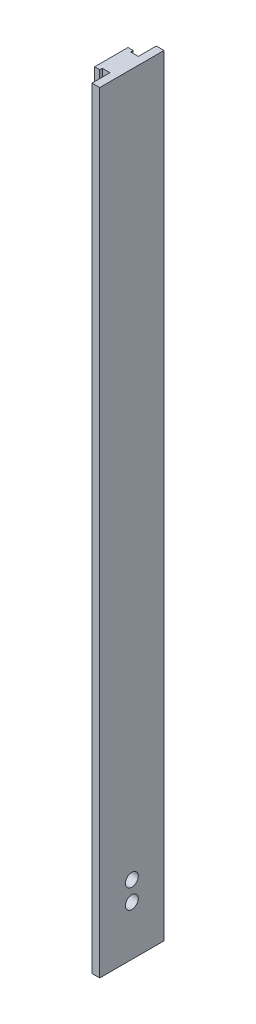
SolidWorks part; units mm, degrees
ref_plane "Alzado" through (0, 0, 0) normal (0, 0, 1) x (1, 0, 0)
ref_plane "Planta" through (0, 0, 0) normal (0, 1, 0) x (1, 0, 0)
ref_plane "Vista lateral" through (0, 0, 0) normal (1, 0, 0) x (0, 0, -1)
sketch "Croquis1" plane through (0, 0, 0) normal (1, 0, 0) x (0, 0, -1)
  line L1 (-10.5505, 28.7844) -> (14.4495, 28.7844)
  line L2 (-10.5505, 28.7844) -> (-10.5505, -271.2156)
  line L3 (-10.5505, -271.2156) -> (14.4495, -271.2156)
  line L4 (14.4495, 28.7844) -> (14.4495, -271.2156)
  dimension "D1" = 25
  dimension "D2" = 300
extrude "Saliente-Extruir1" add sketch "Croquis1" along normal blind 8
sketch "Croquis2" plane through (0, 28.7844, 0) normal (0, 1, 0) x (1, 0, 0)
  line L0 (0, 1.9495) -> (8, 1.9495) construction
  line L1 (0, 14.4495) -> (0, -10.5505) construction
  line L2 (8, 14.4495) -> (8, -10.5505) construction
  line L3 (2, 8.452) -> (2, 7.452)
  line L4 (0, 8.452) -> (2, 8.452)
  line L5 (2, 7.452) -> (5, 7.452)
  line L6 (5, 7.452) -> (5, 14.4495)
  line L7 (8, 14.4495) -> (0, 14.4495) construction
  line L8 (5, 14.4495) -> (0, 14.4495)
  line L9 (0, 14.4495) -> (0, 8.452)
  line L12 (5, -10.5505) -> (0, -10.5505)
  line L13 (5, -3.5529) -> (5, -10.5505)
  line L14 (2, -3.5529) -> (5, -3.5529)
  line L15 (2, -4.5529) -> (2, -3.5529)
  line L16 (0, -4.5529) -> (2, -4.5529)
  line L17 (0, -10.5505) -> (0, -4.5529)
  dimension "D1" = 2
  dimension "D2" = 3
  dimension "D3" = 5.5024
  dimension "D4" = 1
extrude "Cortar-Extruir1" cut sketch "Croquis2" against normal through all
sketch "Croquis3" plane through (8, 0, 0) normal (1, 0, 0) x (0, 0, -1)
  circle A0 centre (1.9495, -251.876) radius 2.5
  circle A1 centre (1.9495, -244.376) radius 2.5
  dimension "D1" = 5
  dimension "D2" = 5
  dimension "D3" = 7.5
extrude "Cortar-Extruir2" cut sketch "Croquis3" against normal through all
